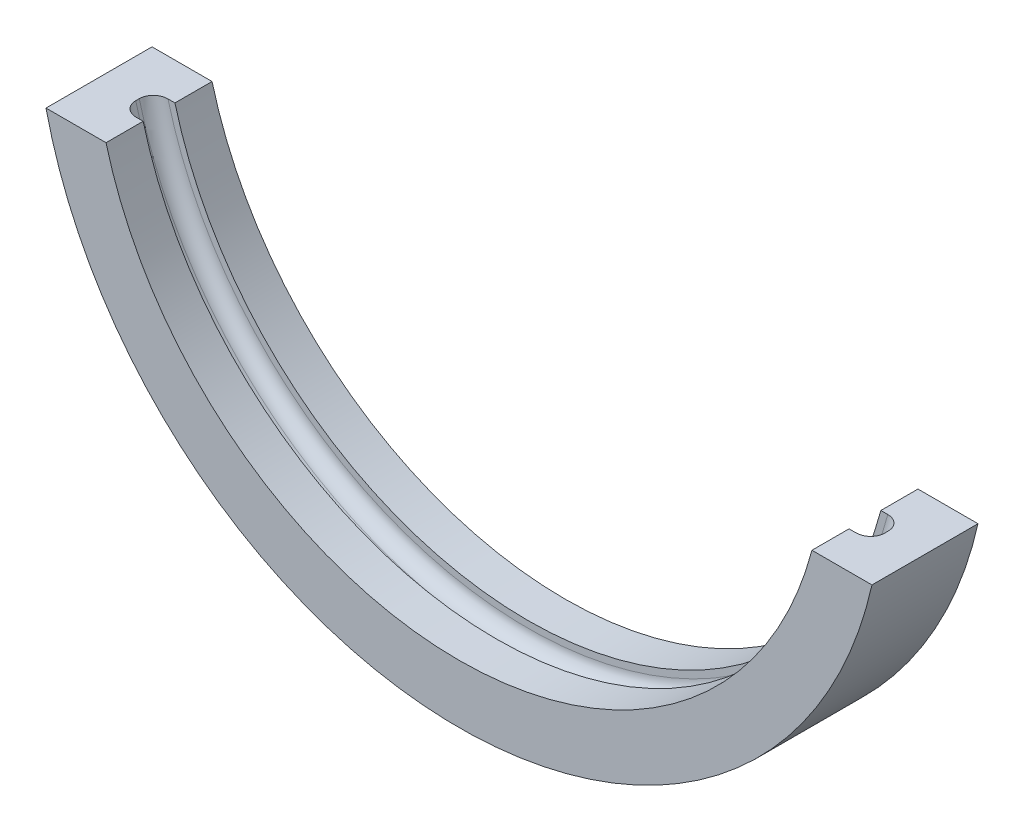
SolidWorks part; units mm, degrees
material "ABS"
ref_plane "Front Plane" through (0, 0, 0) normal (0, 0, 1) x (1, 0, 0)
ref_plane "Top Plane" through (0, 0, 0) normal (0, 1, 0) x (1, 0, 0)
ref_plane "Right Plane" through (0, 0, 0) normal (1, 0, 0) x (0, 0, -1)
sketch "Sketch1" plane through (0, 0, 0) normal (0, 0, 1) x (1, 0, 0)
  line L0 (-69.342, 76.073) -> (-76.073, 76.073)
  line L1 (69.342, 76.073) -> (76.073, 76.073)
  circle A0 centre (0, 76.073) radius 76.073
  circle A1 centre (0, 76.073) radius 69.342
  dimension "D1" = 152.146
  dimension "D2" = 138.684
extrude "Boss-Extrude1" add sketch "Sketch1" along normal blind 5.715 contours A1 L0 A0 L1
sketch "Sketch3" plane through (0, 0, 5.715) normal (0, 0, 1) x (1, 0, 0)
  line L0 (-65.5955, 76.073) -> (-76.073, 76.073)
  line L1 (65.5955, 76.073) -> (76.073, 76.073)
  circle A0 centre (0, 76.073) radius 76.073
  circle A1 centre (0, 76.073) radius 65.5955
  arc M3 (69.342, 76.073) -> (-69.342, 76.073) centre (0, 76.073) cw
  line M4 (-69.342, 76.073) -> (-76.073, 76.073)
  arc M5 (-76.073, 76.073) -> (76.073, 76.073) centre (0, 76.073) ccw
  line M6 (76.073, 76.073) -> (69.342, 76.073)
  dimension "D1" = 131.191
extrude "Boss-Extrude2" add sketch "Sketch3" along normal blind 6.6675 contours A1 L0 L1 M3 | M6 M3 M4 M5
sketch "Sketch4" plane through (0, 0, 0) normal (0, 0, -1) x (-1, 0, 0)
  line L0 (-65.5955, 76.073) -> (-76.073, 76.073)
  line L1 (65.5955, 76.073) -> (76.073, 76.073)
  circle A0 centre (0, 76.073) radius 76.073
  circle A1 centre (0, 76.073) radius 65.5955
  arc M3 (69.342, 76.073) -> (-69.342, 76.073) centre (0, 76.073) cw
  line M4 (-69.342, 76.073) -> (-76.073, 76.073)
  arc M5 (-76.073, 76.073) -> (76.073, 76.073) centre (0, 76.073) ccw
  line M6 (76.073, 76.073) -> (69.342, 76.073)
extrude "Boss-Extrude3" add sketch "Sketch4" along normal blind 6.6675 contours A1 L0 L1 M3 | M6 M3 M4 M5
fillet "Fillet1" radius 2.54 2 edges at (0, 6.731, 0) (0, 6.731, 5.715)
sketch "Sketch5" plane through (0, 0, 0) normal (0, 1, 0) x (1, 0, 0)
  line L0 (64.2819, -2.8575) -> (-64.2819, -2.8575) construction
  circle A0 centre (0, -2.8575) radius 1.524
  dimension "D1" = 3.048
extrude "Cut-Extrude1" cut sketch "Sketch5" along normal blind 6.35
sketch "Sketch6" plane through (0, 0, 12.3825) normal (0, 0, 1) x (1, 0, 0)
  line L0 (-75.9355, 71.501) -> (-69.3315, 71.501)
  line L5 (0, 0) -> (0, 90.126) construction
  line L13 (-75.9355, 59.309) -> (-63.4172, 59.309)
  line L14 (-75.9355, 71.501) -> (-75.9355, 59.309)
  line L17 (-69.3315, 59.309) -> (-69.3315, 71.501)
  line L18 (69.3315, 59.309) -> (69.3315, 71.501)
  line L19 (75.9355, 71.501) -> (69.3315, 71.501)
  line L24 (75.9355, 71.501) -> (75.9355, 59.309)
  line L25 (75.9355, 59.309) -> (63.4172, 59.309)
  line L26 (-65.5955, 76.073) -> (-76.073, 76.073) construction
  arc A0 (-65.5955, 76.073) -> (65.5955, 76.073) centre (0, 76.073) ccw construction
  arc A1 (-76.073, 76.073) -> (76.073, 76.073) centre (0, 76.073) ccw construction
  dimension "D1" = 4.572
  dimension "D4" = 12.192
extrude "Cut-Extrude2" cut sketch "Sketch6" against normal through all
sketch "Sketch7" [suppressed] plane through (0, 0, 12.3825) normal (0, 0, 1) x (1, 0, 0)
  line L0 (-69.7959, 69.977) -> (-75.8284, 69.977) construction
  line L1 (-72.8121, 69.977) -> (-85.9884, 69.977)
  line L2 (-72.8121, 69.977) -> (-72.8121, 79.2871)
  line L3 (-72.8121, 79.2871) -> (-85.9884, 79.2871)
  line L4 (-85.9884, 69.977) -> (-85.9884, 79.2871)
  line L5 (0, 20.0433) -> (0, 96.673) construction
  line L6 (72.8121, 79.2871) -> (85.9884, 79.2871)
  line L7 (85.9884, 69.977) -> (85.9884, 79.2871)
  line L8 (72.8121, 69.977) -> (85.9884, 69.977)
  line L9 (72.8121, 69.977) -> (72.8121, 79.2871)
extrude "Cut-Extrude3" [suppressed] cut sketch "Sketch7" against normal through all contours L2 L1 L4 L3 | L6 L7 L8 L9
